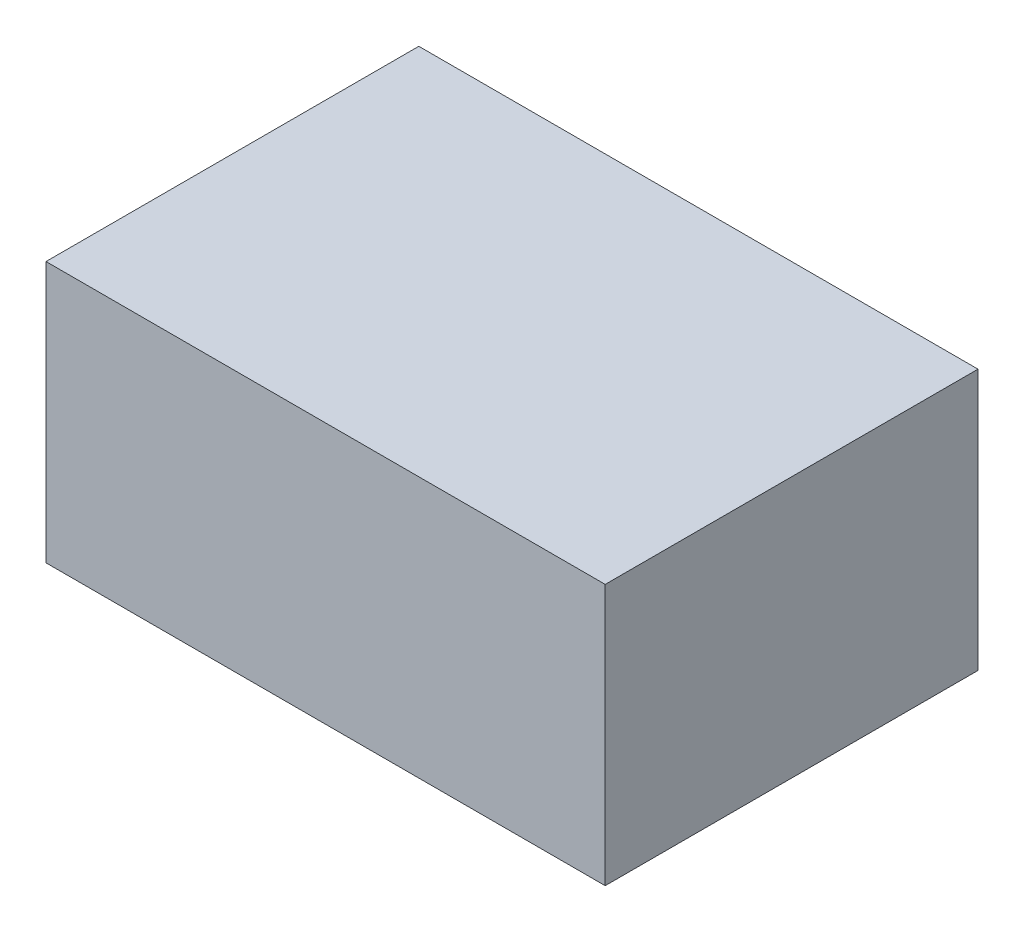
SolidWorks part; units mm, degrees
ref_plane "Спереди" through (0, 0, 0) normal (0, 0, 1) x (1, 0, 0)
ref_plane "Сверху" through (0, 0, 0) normal (0, 1, 0) x (1, 0, 0)
ref_plane "Справа" through (0, 0, 0) normal (1, 0, 0) x (0, 0, -1)
sketch "Эскиз1" plane through (0, 0, 0) normal (0, 0, 1) x (1, 0, 0)
  line L1 (-67.6866, 658.1173) -> (1432.3134, 658.1173)
  line L2 (-67.6866, 658.1173) -> (-67.6866, -41.8827)
  line L3 (-67.6866, -41.8827) -> (1432.3134, -41.8827)
  line L4 (1432.3134, 658.1173) -> (1432.3134, -41.8827)
extrude "Бобышка-Вытянуть1" add sketch "Эскиз1" along normal blind 1000
